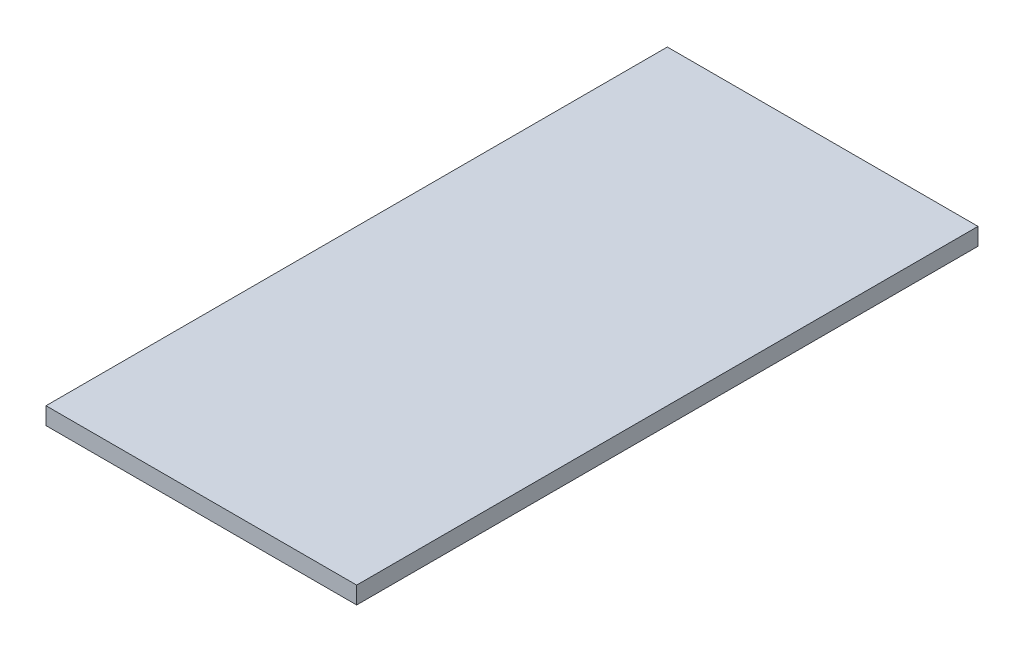
SolidWorks part; units mm, degrees
ref_plane "Plan de face" through (0, 0, 0) normal (0, 0, 1) x (1, 0, 0)
ref_plane "Plan de dessus" through (0, 0, 0) normal (0, 1, 0) x (1, 0, 0)
ref_plane "Plan de droite" through (0, 0, 0) normal (1, 0, 0) x (0, 0, -1)
sketch "Esquisse1" plane through (0, 0, 0) normal (0, 1, 0) x (1, 0, 0)
  line L0 (0, 42.0538) -> (0, -48.8341) construction
  line L1 (-85.0762, 0) -> (94.6009, 0) construction
  line L3 (27, -54) -> (-27, -54)
  line L4 (27, -54) -> (27, 54)
  line L5 (27, 54) -> (-27, 54)
  line L6 (-27, -54) -> (-27, 54)
  line L7 (27, -54) -> (-27, 54) construction
  line L8 (27, 54) -> (-27, -54) construction
  point P5 (0, 0)
  dimension "D1" = 108
  dimension "D2" = 54
extrude "Boss.-Extru.1" add sketch "Esquisse1" along normal blind 3
